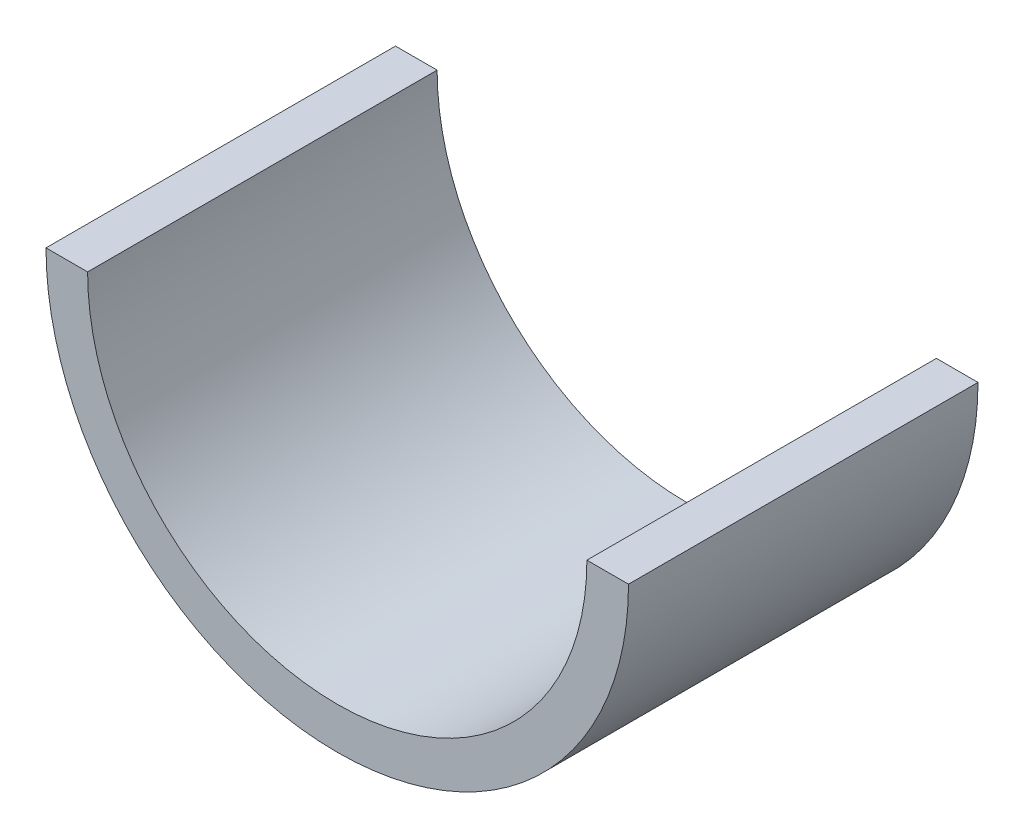
SolidWorks part; units mm, degrees
ref_plane "Спереди" through (0, 0, 0) normal (0, 0, 1) x (1, 0, 0)
ref_plane "Сверху" through (0, 0, 0) normal (0, 1, 0) x (1, 0, 0)
ref_plane "Справа" through (0, 0, 0) normal (1, 0, 0) x (0, 0, -1)
other "Configuration Table"
sketch "Эскиз1" plane through (0, 0, 0) normal (0, 0, 1) x (1, 0, 0)
  line L0 (-35, 0) -> (35, 0)
  arc A0 (-30, 0) -> (30, 0) centre (0, 0) ccw
  arc A1 (-35, 0) -> (35, 0) centre (0, 0) ccw
  circle A2 centre (0, 0) radius 35 construction
  circle A3 centre (0, 0) radius 30 construction
  dimension "D1" = 60
  dimension "D2" = 5
extrude "Бобышка-Вытянуть1" add sketch "Эскиз1" along normal blind 42 contours L0 A1 A0
